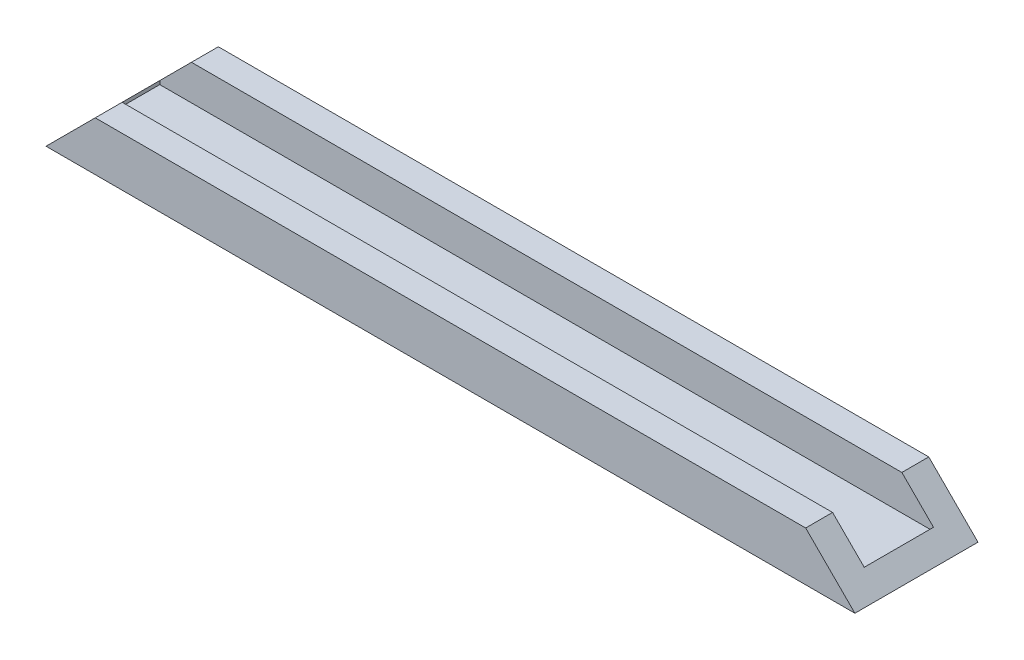
SolidWorks part; units mm, degrees
material "Copper"
ref_plane "Front Plane" through (0, 0, 0) normal (0, 0, 1) x (1, 0, 0)
ref_plane "Top Plane" through (0, 0, 0) normal (0, 1, 0) x (1, 0, 0)
ref_plane "Right Plane" through (0, 0, 0) normal (1, 0, 0) x (0, 0, -1)
sketch "Sketch1" plane through (0, 0, 0) normal (0, 1, 0) x (1, 0, 0)
  line L1 (0, 0) -> (146.05, 0)
  line L2 (0, 0) -> (0, 22.225)
  line L3 (0, 22.225) -> (146.05, 22.225)
  line L4 (146.05, 0) -> (146.05, 22.225)
  dimension "D1" = 146.05
  dimension "D2" = 22.225
extrude "Base Extrude" add sketch "Sketch1" along normal blind 8.89
sketch "Sketch3" plane through (0, 8.89, 0) normal (0, 1, 0) x (1, 0, 0)
  line L1 (3.175, 17.3673) -> (142.875, 17.3672)
  line L2 (3.175, 17.3673) -> (3.175, 4.8577)
  line L3 (3.175, 4.8577) -> (142.875, 4.8577)
  line L4 (142.875, 17.3672) -> (142.875, 4.8577)
  line L5 (0, 22.225) -> (0, 0) construction
  line L6 (146.05, 0) -> (146.05, 22.225) construction
  line L8 (3.175, 11.1125) -> (142.875, 11.1125) construction
  line L9 (146.05, 11.1125) -> (0, 11.1125) construction
  dimension "D1" = 12.5095
  dimension "D2" = 139.7
  dimension "D3" = 3.175
extrude "Piece Cut" cut sketch "Sketch3" against normal blind 6.35
sketch "Sketch4" plane through (0, 0, -22.225) normal (0, 0, -1) x (-1, 0, 0)
  line L0 (0, 0) -> (-8.89, 8.89)
  line L1 (-146.05, 8.89) -> (0, 8.89) construction
  line L2 (0, 0) -> (0, 8.89)
  line L3 (0, 8.89) -> (-8.89, 8.89)
  line L4 (-73.025, 0) -> (-73.025, 8.89) construction
  line L5 (-146.05, 0) -> (0, 0) construction
  line L6 (-146.05, 8.89) -> (-137.16, 8.89)
  line L7 (-146.05, 0) -> (-146.05, 8.89)
  line L8 (-146.05, 0) -> (-137.16, 8.89)
  dimension "D1" = 45
extrude "Corner Cut" cut sketch "Sketch4" against normal through all
